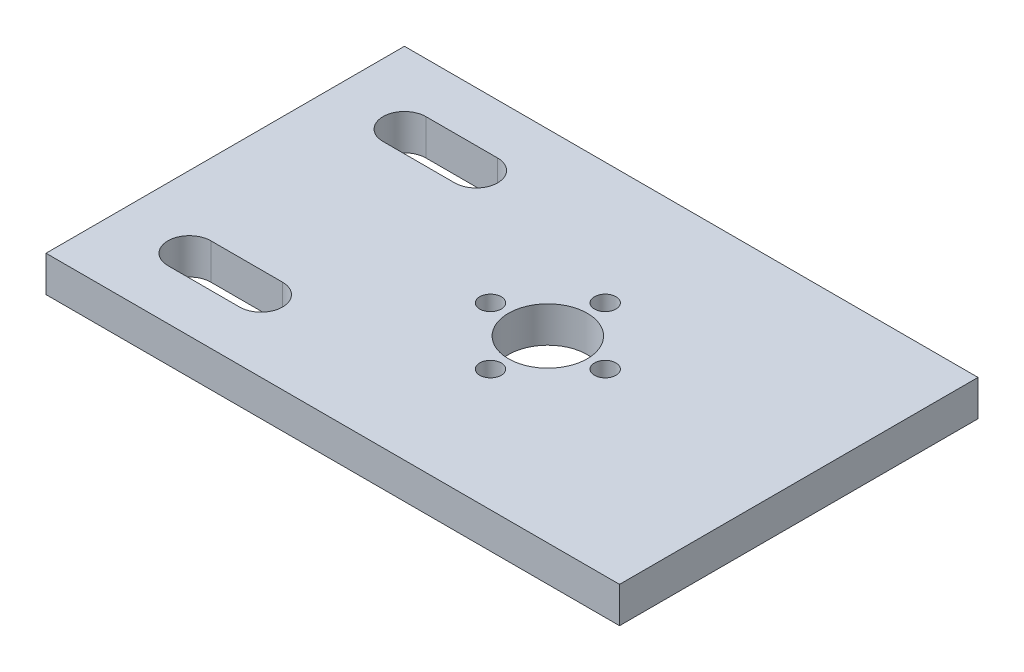
SolidWorks part; units mm, degrees
ref_plane "Front Plane" through (0, 0, 0) normal (0, 0, 1) x (1, 0, 0)
ref_plane "Top Plane" through (0, 0, 0) normal (0, 1, 0) x (1, 0, 0)
ref_plane "Right Plane" through (0, 0, 0) normal (1, 0, 0) x (0, 0, -1)
sketch "Sketch1" plane through (0, 0, 0) normal (0, 1, 0) x (1, 0, 0)
  line L0 (10, 40) -> (20, 40) construction
  line L1 (0, 0) -> (80, 0)
  line L2 (0, 0) -> (0, 50)
  line L3 (0, 50) -> (80, 50)
  line L4 (80, 0) -> (80, 50)
  line L5 (10, 43) -> (20, 43)
  line L6 (10, 37) -> (20, 37)
  line L7 (10, 10) -> (20, 10) construction
  line L8 (10, 13) -> (20, 13)
  line L9 (10, 7) -> (20, 7)
  arc A0 (10, 43) -> (10, 37) centre (10, 40) ccw
  arc A1 (20, 37) -> (20, 43) centre (20, 40) ccw
  arc A2 (10, 13) -> (10, 7) centre (10, 10) ccw
  arc A3 (20, 7) -> (20, 13) centre (20, 10) ccw
  circle A4 centre (45, 25) radius 5.5
  point P7 (15, 40)
  point P14 (15, 10)
  dimension "D5" = 3
  dimension "D7" = 3
  dimension "D10" = 11
  dimension "D1" = 80
  dimension "D2" = 50
  dimension "D3" = 15
  dimension "D4" = 10
  dimension "D6" = 10
  dimension "D8" = 10
  dimension "D9" = 35
extrude "Boss-Extrude1" add sketch "Sketch1" along normal blind 5
sketch "Sketch2" plane through (0, 0, 0) normal (0, -1, 0) x (-1, 0, 0)
  circle A0 centre (-45, 17) radius 1.5
  circle A1 centre (-53, 25) radius 1.5
  circle A2 centre (-37, 25) radius 1.5
  circle A3 centre (-45, 33) radius 1.5
  point P12 (0, 0)
sketch "Sketch3" plane through (0, 0, 0) normal (0, -1, 0) x (1, 0, 0)
  circle A0 centre (45, -17) radius 1.5
  circle A1 centre (53, -25) radius 1.5
  circle A2 centre (45, -33) radius 1.5
  circle A3 centre (37, -25) radius 1.5
  dimension "D1" = 3
  dimension "D2" = 3
  dimension "D3" = 3
  dimension "D4" = 3
extrude "Cut-Extrude1" cut sketch "Sketch3" against normal blind 5
